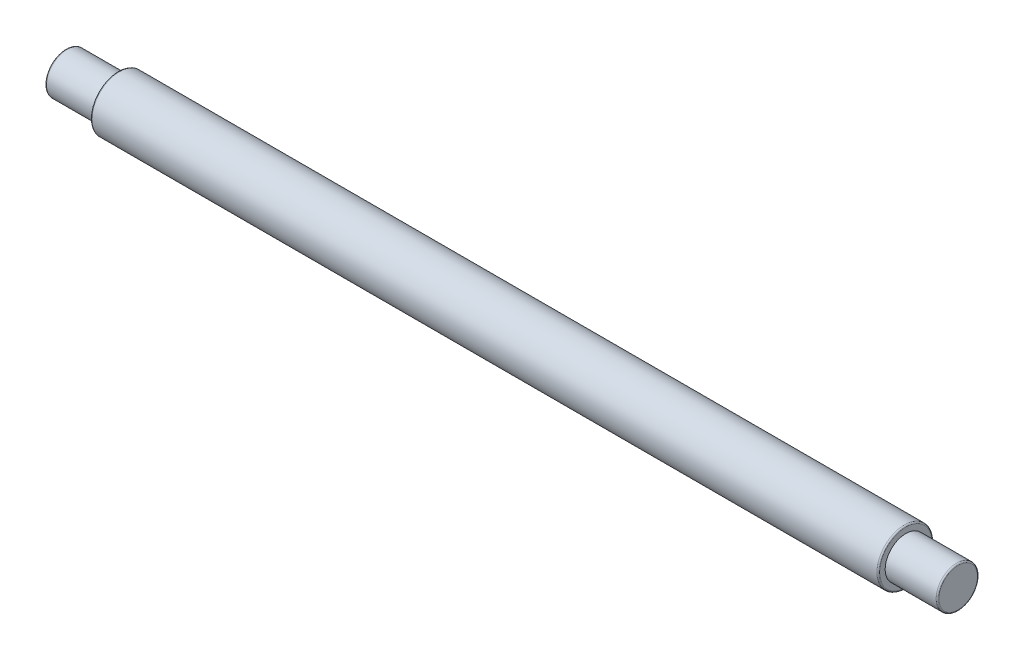
SolidWorks part; units mm, degrees
ref_plane "Ön Düzlem" through (0, 0, 0) normal (0, 0, 1) x (1, 0, 0)
ref_plane "Üst Düzlem" through (0, 0, 0) normal (0, 1, 0) x (1, 0, 0)
ref_plane "Sağ Düzlem" through (0, 0, 0) normal (1, 0, 0) x (0, 0, -1)
sketch "Çizim1" plane through (0, 0, 0) normal (0, 0, 1) x (1, 0, 0)
  line L0 (-324, 0) -> (324, 0) construction
  line L1 (-324, 0) -> (-324, 15)
  line L2 (-324, 15) -> (-286, 15)
  line L3 (-286, 15) -> (-286, 20)
  line L4 (-286, 20) -> (286, 20)
  line L5 (286, 20) -> (286, 15)
  line L6 (286, 15) -> (324, 15)
  line L7 (324, 15) -> (324, 0)
  line L8 (-324, 0) -> (324, 0)
  point P3 (0, 0)
  dimension "D1" = 572
  dimension "D2" = 15
  dimension "D3" = 20
  dimension "D4" = 38
  dimension "D5" = 38
revolve "Döndür1" add sketch "Çizim1" angle 360 about L0
fillet "Radyus1" radius 1 4 edges at (324, -15, 0) (286, -20, 0) (-286, -20, 0) (-324, -15, 0)
